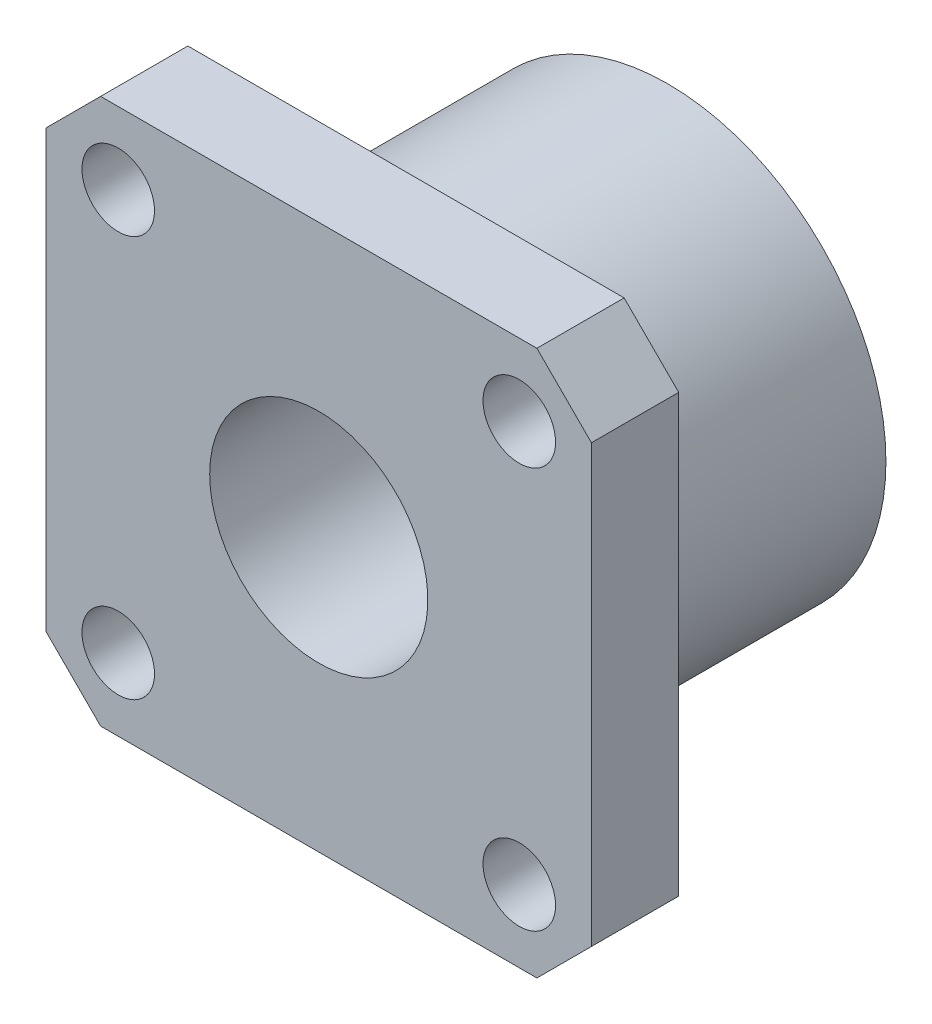
SolidWorks part; units mm, degrees
ref_plane "前视基准面" through (0, 0, 0) normal (0, 0, 1) x (1, 0, 0)
ref_plane "上视基准面" through (0, 0, 0) normal (0, 1, 0) x (1, 0, 0)
ref_plane "右视基准面" through (0, 0, 0) normal (1, 0, 0) x (0, 0, -1)
sketch "草图1" plane through (0, 0, 0) normal (0, 0, 1) x (1, 0, 0)
  line L1 (25, -25) -> (-25, -25)
  line L2 (25, -25) -> (25, 25)
  line L3 (25, 25) -> (-25, 25)
  line L4 (-25, -25) -> (-25, 25)
  line L5 (25, -25) -> (-25, 25) construction
  line L6 (25, 25) -> (-25, -25) construction
  circle A0 centre (-18.3848, 18.3848) radius 3.325
  circle A2 centre (18.3848, 18.3848) radius 3.325
  circle A3 centre (18.3848, -18.3848) radius 3.325
  circle A4 centre (-18.3848, -18.3848) radius 3.325
  point P0 (0, 0)
  dimension "D2" = 6.65
  dimension "D3" = 26
  dimension "D1" = 50
  dimension "D4" = 4
extrude "凸台-拉伸1" add sketch "草图1" along normal blind 8
chamfer "倒角1" distance 5 angle 45 4 edges at (-25, -25, 4) (25, -25, 4) (25, 25, 4) (-25, 25, 4)
sketch "草图2" plane through (0, 0, 0) normal (0, 0, -1) x (-1, 0, 0)
  circle A0 centre (0, 0) radius 20
  circle A1 centre (0, 0) radius 10
  dimension "D1" = 40
  dimension "D2" = 20
extrude "凸台-拉伸2" add sketch "草图2" along normal blind 24
sketch "草图3" plane through (0, 0, 0) normal (0, 0, -1) x (-1, 0, 0)
  circle A1 centre (0, 0) radius 10
  circle A2 centre (0, 0) radius 10
  dimension "D1" = 0
extrude "切除-拉伸1" cut sketch "草图3" against normal through all
